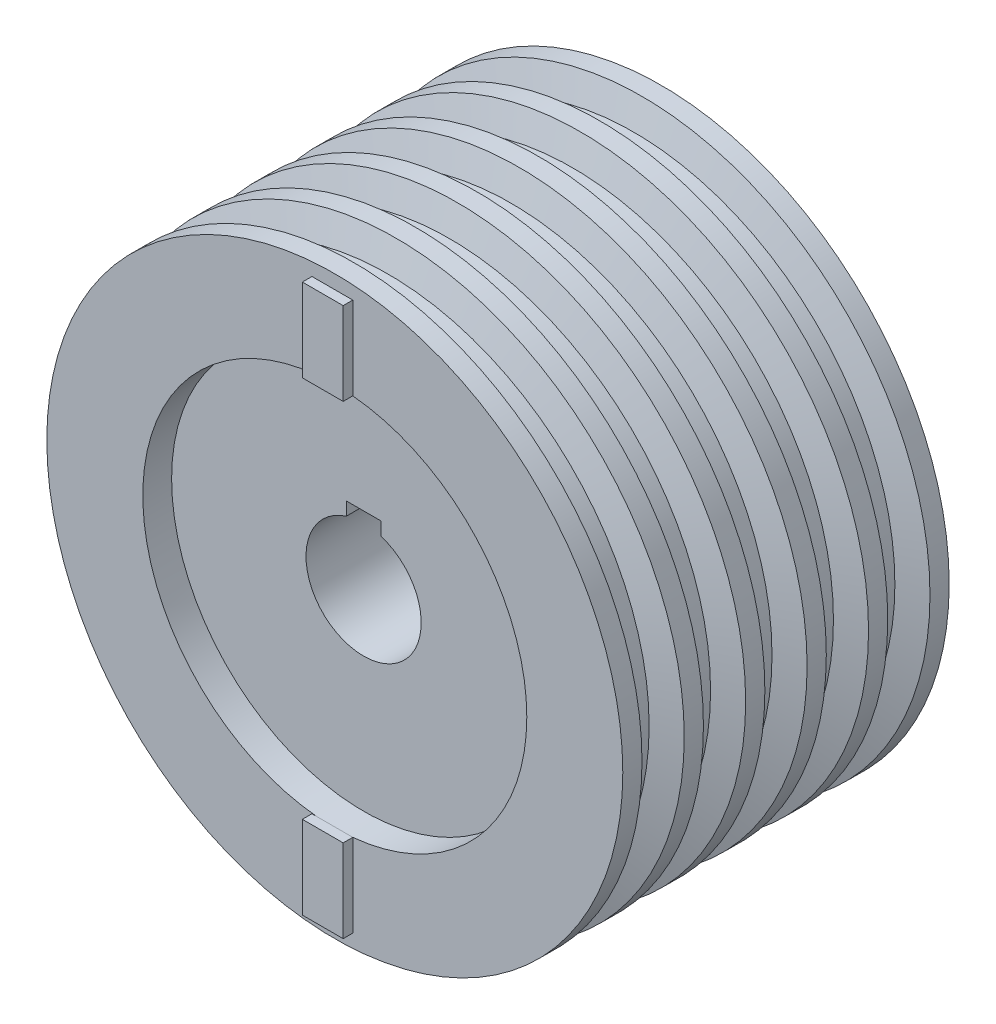
SolidWorks part; units mm, degrees
material "Gray Cast Iron"
ref_plane "Front Plane" through (0, 0, 0) normal (0, 0, 1) x (1, 0, 0)
ref_plane "Top Plane" through (0, 0, 0) normal (0, 1, 0) x (1, 0, 0)
ref_plane "Right Plane" through (0, 0, 0) normal (1, 0, 0) x (0, 0, -1)
sketch "Sketch1" plane through (0, 0, 0) normal (0, 0, 1) x (1, 0, 0)
  circle A0 centre (0, 0) radius 150
  dimension "D1" = 300
extrude "Boss-Extrude1" add sketch "Sketch1" along normal mid plane 170
sketch "Sketch3" plane through (0, 0, 85) normal (0, 0, 1) x (1, 0, 0)
  circle A0 centre (0, 0) radius 30
  dimension "D1" = 60
extrude "Cut-Extrude1" cut sketch "Sketch3" against normal through all
sketch "Sketch4" plane through (0, 0, 85) normal (0, 0, 1) x (1, 0, 0)
  circle A0 centre (0, 0) radius 100
  circle A1 centre (0, 0) radius 30 construction
  circle A2 centre (0, 0) radius 30
  dimension "D1" = 200
extrude "Cut-Extrude2" cut sketch "Sketch4" against normal blind 15
mirror "Mirror1" about plane through (0, 0, 0) normal (0, 0, 1) of "Cut-Extrude2"
sketch "Sketch5" plane through (0, 0, 70) normal (0, 0, 1) x (1, 0, 0)
  line L1 (-9, 24.5) -> (9, 24.5)
  line L2 (-9, 24.5) -> (-9, 35.5)
  line L3 (-9, 35.5) -> (9, 35.5)
  line L4 (9, 24.5) -> (9, 35.5)
  line L5 (-9, 24.5) -> (9, 35.5) construction
  line L6 (-9, 35.5) -> (9, 24.5) construction
  circle A0 centre (0, 0) radius 30 construction
  point P0 (0, 30)
  dimension "D1" = 18
  dimension "D2" = 11
extrude "Cut-Extrude3" cut sketch "Sketch5" against normal through all
sketch "Sketch9" plane through (0, 0, 0) normal (0, 1, 0) x (1, 0, 0)
  line L0 (150, 75) -> (136, 70.7198)
  line L1 (150, -85) -> (150, 85) construction
  line L2 (136, 70.7198) -> (136, 57.2802)
  line L3 (136, 57.2802) -> (150, 53)
  line L4 (150, 53) -> (150, 75)
  line L5 (150, 85) -> (-150, 85) construction
  line L6 (104.62, 48) -> (276.5217, 48) construction
  line L7 (276.5217, 48) -> (276.5217, 16) construction
  line L8 (276.5217, 16) -> (99.1192, 16) construction
  line L9 (99.1192, 16) -> (99.1192, -20.2139) construction
  line L10 (99.1192, -20.2139) -> (276.5217, -20.2139) construction
  line L11 (276.5217, -20.2139) -> (276.5217, -48) construction
  line L12 (276.5217, -48) -> (99.0813, -48) construction
  line L13 (150, 43) -> (150, 21)
  line L14 (136, 38.7198) -> (150, 43)
  line L15 (136, 25.2802) -> (136, 38.7198)
  line L16 (150, 21) -> (136, 25.2802)
  line L17 (150, 11) -> (136, 6.7198)
  line L18 (136, 6.7198) -> (136, -6.7198)
  line L19 (136, -6.7198) -> (150, -11)
  line L20 (150, -11) -> (150, 11)
  line L21 (150, -21) -> (150, -43)
  line L22 (136, -25.2802) -> (150, -21)
  line L23 (136, -38.7198) -> (136, -25.2802)
  line L24 (150, -43) -> (136, -38.7198)
  line L25 (150, -53) -> (136, -57.2802)
  line L26 (136, -57.2802) -> (136, -70.7198)
  line L27 (136, -70.7198) -> (150, -75)
  line L28 (150, -75) -> (150, -53)
  line L29 (0, 0) -> (0, 124.531) construction
  dimension "D1" = 10
  dimension "D2" = 22
  dimension "D3" = 14
  dimension "D4" = 73
  dimension "D5" = 73
  dimension "D6" = 5
  dimension "D7" = 5
  dimension "D8" = 5
revolve "Cut-Revolve2" cut sketch "Sketch9" angle 360 about L29
sketch "Sketch10" plane through (0, 0, 85) normal (0, 0, 1) x (1, 0, 0)
  line L0 (0, 0) -> (262.9038, 0) construction
  line L1 (-11.903, 142.7797) -> (9.3539, 142.7797)
  line L2 (-11.903, 142.7797) -> (-11.903, 99.5616)
  line L3 (-11.903, 99.5616) -> (9.3539, 99.5616)
  line L4 (9.3539, 142.7797) -> (9.3539, 99.5616)
  line L5 (9.3539, -142.7797) -> (9.3539, -99.5616)
  line L6 (-11.903, -99.5616) -> (9.3539, -99.5616)
  line L7 (-11.903, -142.7797) -> (-11.903, -99.5616)
  line L8 (-11.903, -142.7797) -> (9.3539, -142.7797)
  circle A0 centre (0, 0) radius 100 construction
extrude "Boss-Extrude2" add sketch "Sketch10" along normal blind 5
